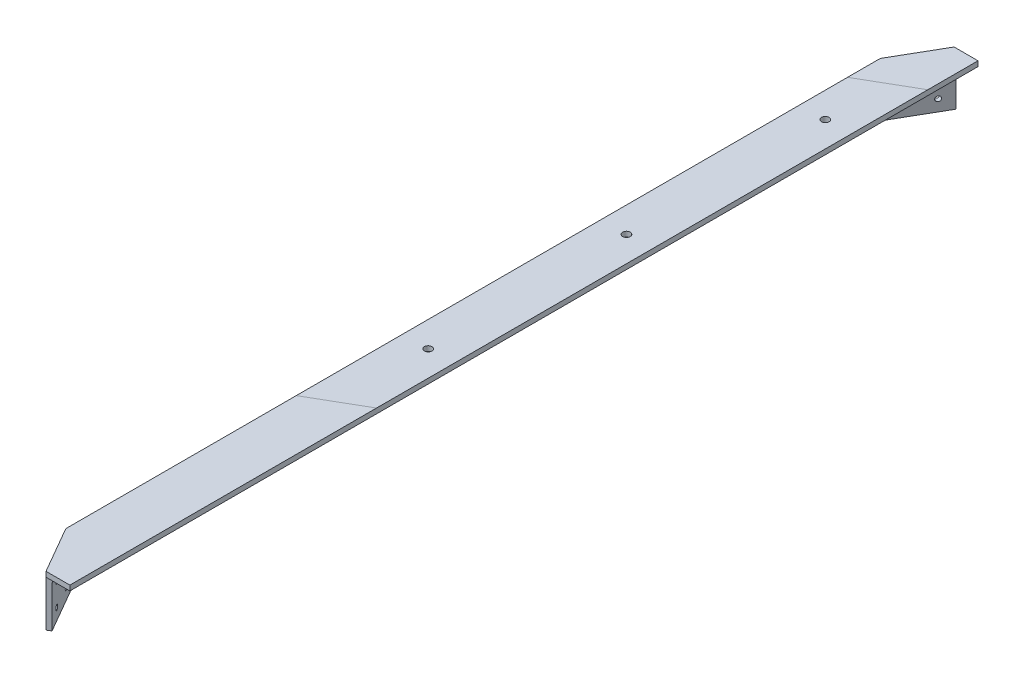
SolidWorks part; units mm, degrees
material "1.0116 (S235J2G3)"
ref_plane "Front Plane" through (0, 0, 0) normal (0, 0, 1) x (1, 0, 0)
ref_plane "Top Plane" through (0, 0, 0) normal (0, 1, 0) x (1, 0, 0)
ref_plane "Right Plane" through (0, 0, 0) normal (1, 0, 0) x (0, 0, -1)
sketch "Sketch1" plane through (0, 0, 0) normal (0, 0, 1) x (1, 0, 0)
  line L0 (-8, 8) -> (72, 8)
  line L1 (72, 8) -> (72, 0)
  line L2 (72, 0) -> (0, 0)
  line L3 (0, 0) -> (0, -72)
  line L4 (0, -72) -> (-8, -72)
  line L5 (-8, -72) -> (-8, 8)
  dimension "D1" = 80
  dimension "D2" = 80
  dimension "D3" = 8
  dimension "D4" = 8
extrude "Boss-Extrude1" add sketch "Sketch1" along normal blind 640
sketch "Sketch3" plane through (0, 0, 0) normal (0, 1, 0) x (1, 0, 0)
  line L0 (-8, -640) -> (34.5, -713.6122)
  line L1 (34.5, -713.6122) -> (72, -713.6122)
  line L2 (72, -713.6122) -> (72, -640)
  line L3 (72, -640) -> (-8, -640)
  line L4 (-8, -640) -> (-8, 0) construction
  dimension "D1" = 210
  dimension "D2" = 85
extrude "Boss-Extrude2" add sketch "Sketch3" along normal blind 8
sketch "Sketch4" plane through (0, 0, 0) normal (0, -1, 0) x (1, 0, 0)
  line L0 (-8, 640) -> (34.5, 713.6122)
  line L1 (34.5, 713.6122) -> (40.5, 710.1481)
  line L2 (40.5, 710.1481) -> (0, 640)
  line L3 (-8, 640) -> (0, 640) construction
  line L4 (0, 640) -> (-8, 640)
  dimension "D1" = 8
extrude "Boss-Extrude3" add sketch "Sketch4" along normal blind 72
sketch "Sketch6" plane through (-277.1281, 0, 160) normal (0.866, 0, -0.5) x (-0.5, 0, -0.866)
  line L0 (-635.2563, -36) -> (-554.2563, -36) construction
  line L1 (-635.2563, -72) -> (-635.2563, 0) construction
  line L2 (-554.2563, -72) -> (-554.2563, 0) construction
  line L3 (-594.7563, 0) -> (-594.7563, -72) construction
  line L4 (-554.2563, 0) -> (-635.2563, 0) construction
  line L5 (-554.2563, -72) -> (-635.2563, -72) construction
  circle A0 centre (-615.0063, -18) radius 4
  circle A1 centre (-574.5063, -18) radius 4
  circle A2 centre (-574.5063, -54) radius 4
  circle A3 centre (-615.0063, -54) radius 4
  dimension "D1" = 20.25
  dimension "D3" = 8
  dimension "D2" = 18
extrude "Cut-Extrude1" cut sketch "Sketch6" against normal blind 8
fillet "Fillet1" radius 10 2 edges at (-8, -32, 640) (0, -36, 640)
fillet "Fillet2" radius 8 3 edges at (0, 0, 318.6603) (0.3407, 0, 639.9087) (20.9199, 0, 676.2343)
mirror "Mirror1" about plane through (0, 0, 0) normal (0, 0, 1) of "Boss-Extrude1", "Boss-Extrude2", "Boss-Extrude3", "Cut-Extrude1", "Fillet1", "Fillet2"
sketch "Sketch7" plane through (0, 8, 0) normal (0, 1, 0) x (1, 0, 0)
  line L0 (-8, 588.5705) -> (72, 634.7585)
  line L1 (-8, -637.3205) -> (-8, 637.3205) construction
  line L2 (72, -713.6122) -> (72, 713.6122) construction
  line L3 (72, 634.7585) -> (72, -231.6622)
  line L4 (72, -231.6622) -> (-8, -277.8502)
  line L5 (-8, -277.8502) -> (-8, 588.5705)
  dimension "D1" = 60
  dimension "D2" = 60
  dimension "D3" = 48.75
  dimension "D4" = 481.95
split line "Split Line1"
sketch "Sketch10" plane through (0, 8, 0) normal (0, 1, 0) x (1, 0, 0)
  line L0 (34.5, 713.6122) -> (72, 713.6122) construction
  line L1 (-8, -277.8502) -> (-8, 588.5705) construction
  circle A0 centre (32, 513.6122) radius 6
  circle A1 centre (32, 201.1122) radius 6
  circle A2 centre (32, -110.5122) radius 6
  dimension "D1" = 12
  dimension "D2" = 12
  dimension "D3" = 12
  dimension "D5" = 40
  dimension "D8" = 824.1243
  dimension "D9" = 512.5
  dimension "D4" = 200
  dimension "D6" = 40
  dimension "D7" = 40
extrude "Cut-Extrude2" cut sketch "Sketch10" against normal blind 8
